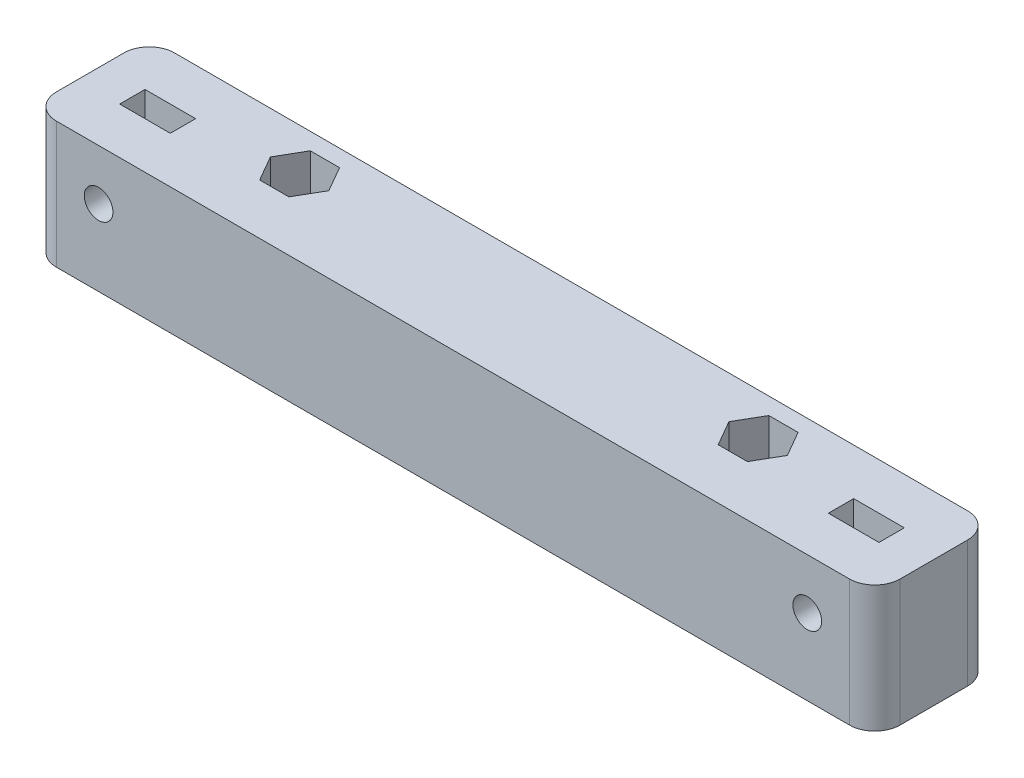
SolidWorks part; units mm, degrees
ref_plane "Front Plane" through (0, 0, 0) normal (0, 0, 1) x (1, 0, 0)
ref_plane "Top Plane" through (0, 0, 0) normal (0, 1, 0) x (1, 0, 0)
ref_plane "Right Plane" through (0, 0, 0) normal (1, 0, 0) x (0, 0, -1)
sketch "Sketch1" plane through (0, 0, 0) normal (0, 1, 0) x (1, 0, 0)
  line L1 (-50, 7) -> (50, 7)
  line L2 (-50, 7) -> (-50, -7)
  line L3 (-50, -7) -> (50, -7)
  line L4 (50, 7) -> (50, -7)
  line L5 (-50, 7) -> (50, -7) construction
  line L6 (-50, -7) -> (50, 7) construction
  circle A0 centre (-27.175, 2) radius 1.7
  circle A1 centre (27.175, 2) radius 1.7
  point P0 (0, 0)
  dimension "D3" = 5
  dimension "D7" = 3.4
  dimension "D8" = 3.4
  dimension "D1" = 14
  dimension "D2" = 100
  dimension "D4" = 5
  dimension "D5" = 27.175
  dimension "D6" = 27.175
extrude "Boss-Extrude1" add sketch "Sketch1" along normal blind 15
sketch "Sketch3" plane through (0, 0, 7) normal (0, 0, 1) x (1, 0, 0)
  line L1 (-50, 15) -> (-50, 0) construction
  line L2 (50, 15) -> (50, 0) construction
  line L3 (-50, 15) -> (50, 15) construction
  circle A0 centre (-42, 9) radius 1.7
  circle A1 centre (42, 9) radius 1.7
  point P10 (0, 0)
  dimension "D5" = 3.4
  dimension "D6" = 3.4
  dimension "D1" = 6
  dimension "D2" = 8
  dimension "D3" = 8
  dimension "D4" = 6
extrude "Cut-Extrude2" cut sketch "Sketch3" against normal through all
sketch "Sketch4" plane through (0, 0, 7) normal (0, 0, 1) x (1, 0, 0)
  line L0 (-45, 10.7321) -> (-45, 16.4519)
  line L2 (-45, 10.7321) -> (-45, 7.2679)
  line L3 (-45, 7.2679) -> (-42, 5.5359)
  line L4 (-42, 5.5359) -> (-39, 7.2679)
  line L5 (-39, 7.2679) -> (-39, 10.7321)
  line L7 (-45, 16.4519) -> (-39, 16.4519)
  line L8 (-39, 16.4519) -> (-39, 10.7321)
  line L9 (0, -7.7) -> (0, 7.7) construction
  line L10 (-39, 10.7321) -> (-40.5, 11.5981) [skipped]
  line L11 (-43.5, 11.5981) -> (-45, 10.7321) [skipped]
  line L12 (39, 16.4519) -> (39, 10.7321)
  line L13 (45, 16.4519) -> (39, 16.4519)
  line L14 (39, 7.2679) -> (39, 10.7321)
  line L15 (42, 5.5359) -> (39, 7.2679)
  line L16 (45, 7.2679) -> (42, 5.5359)
  line L17 (45, 10.7321) -> (45, 7.2679)
  line L18 (45, 10.7321) -> (45, 16.4519)
  arc A0 (-45, 9) -> (-39, 9) centre (-42, 9) ccw construction
  arc A1 (45, 9) -> (39, 9) centre (42, 9) cw construction
  dimension "D1" = 6
extrude "Cut-Extrude3" cut sketch "Sketch4" against normal mid plane 3 from surface at -7 starting at plane "Front Plane"
sketch "Sketch5" plane through (0, 15, 0) normal (0, 1, 0) x (1, 0, 0)
  line L0 (0, -7.7) -> (0, 7.7) construction
  line L1 (-23.7109, 2) -> (-25.4429, 5)
  line L2 (-25.4429, 5) -> (-28.9071, 5)
  line L3 (-28.9071, 5) -> (-30.6391, 2)
  line L4 (-30.6391, 2) -> (-28.9071, -1)
  line L5 (-28.9071, -1) -> (-25.4429, -1)
  line L6 (-25.4429, -1) -> (-23.7109, 2)
  line L7 (25.4429, -1) -> (23.7109, 2)
  line L8 (28.9071, -1) -> (25.4429, -1)
  line L9 (30.6391, 2) -> (28.9071, -1)
  line L10 (28.9071, 5) -> (30.6391, 2)
  line L11 (25.4429, 5) -> (28.9071, 5)
  line L12 (23.7109, 2) -> (25.4429, 5)
  circle A0 centre (-27.175, 2) radius 3 construction
  circle A1 centre (27.175, 2) radius 3 construction
  dimension "D1" = 6
extrude "Cut-Extrude4" cut sketch "Sketch5" against normal blind 6
fillet "Fillet4" radius 3 4 edges at (50, 7.5, -7) (50, 7.5, 7) (-50, 7.5, 7) (-50, 7.5, -7)
